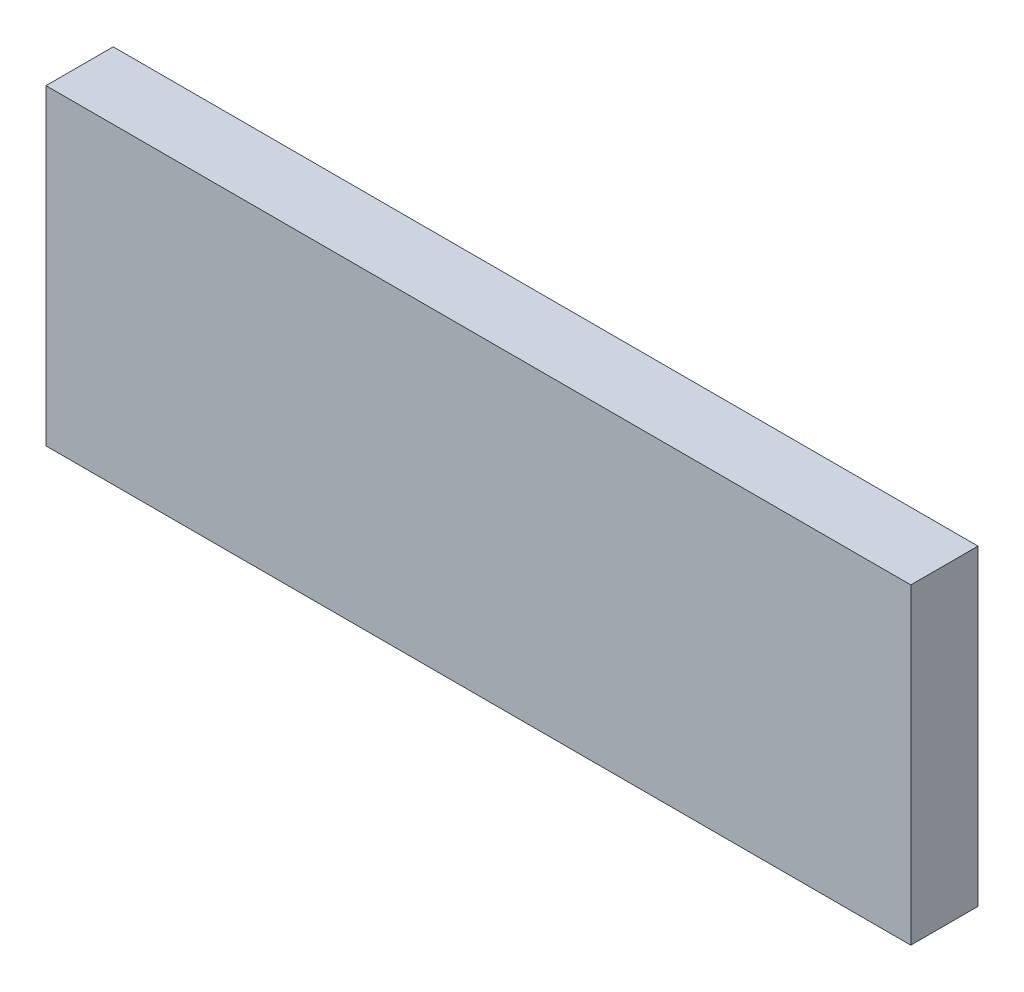
SolidWorks part; units mm, degrees
ref_plane "Plan de face" through (0, 0, 0) normal (0, 0, 1) x (1, 0, 0)
ref_plane "Plan de dessus" through (0, 0, 0) normal (0, 1, 0) x (1, 0, 0)
ref_plane "Plan de droite" through (0, 0, 0) normal (1, 0, 0) x (0, 0, -1)
sketch "Esquisse1" plane through (0, 0, 0) normal (0, 0, 1) x (1, 0, 0)
  line L1 (-36.702, 21.4105) -> (38.488, 21.4105)
  line L2 (-36.702, 21.4105) -> (-36.702, -6.4395)
  line L3 (-36.702, -6.4395) -> (38.488, -6.4395)
  line L4 (38.488, 21.4105) -> (38.488, -6.4395)
  dimension "D1" = 75.19
  dimension "D2" = 27.85
extrude "Boss.-Extru.1" add sketch "Esquisse1" along normal blind 6
sketch "Esquisse2" plane through (38.488, 0, 0) normal (1, 0, 0) x (0, 0, -1)
  line L1 (-6, -6.4395) -> (0, -6.4395)
  line L2 (-6, -6.4395) -> (-6, 21.4105)
  line L3 (-6, 21.4105) -> (0, 21.4105)
  line L4 (0, -6.4395) -> (0, 21.4105)
extrude "Boss.-Extru.2" add sketch "Esquisse2" along normal blind 2
